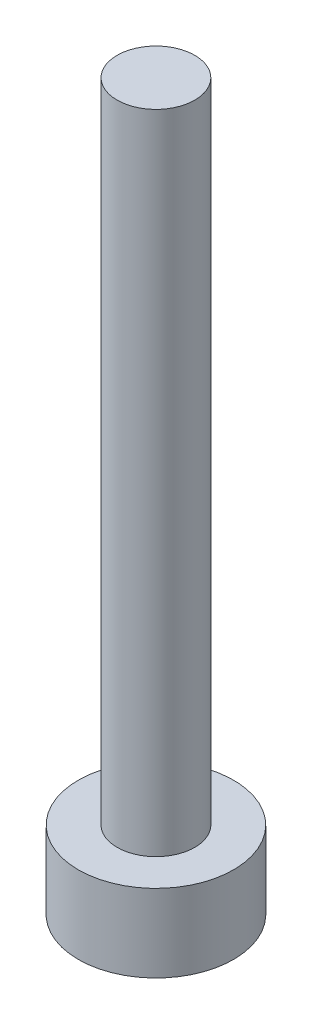
SolidWorks part; units mm, degrees
material "201 退火不锈钢 (SS)"
ref_plane "前视基准面" through (0, 0, 0) normal (0, 0, 1) x (1, 0, 0)
ref_plane "上视基准面" through (0, 0, 0) normal (0, 1, 0) x (1, 0, 0)
ref_plane "右视基准面" through (0, 0, 0) normal (1, 0, 0) x (0, 0, -1)
sketch "草图1" plane through (0, 0, 0) normal (0, 1, 0) x (1, 0, 0)
  circle A0 centre (0, 0) radius 3
  dimension "D1" = 6
extrude "凸台-拉伸1" add sketch "草图1" along normal blind 3
sketch "草图2" plane through (0, 3, 0) normal (0, 1, 0) x (1, 0, 0)
  circle A0 centre (0, 0) radius 1.5
  dimension "D1" = 3
extrude "凸台-拉伸2" add sketch "草图2" along normal blind 25
